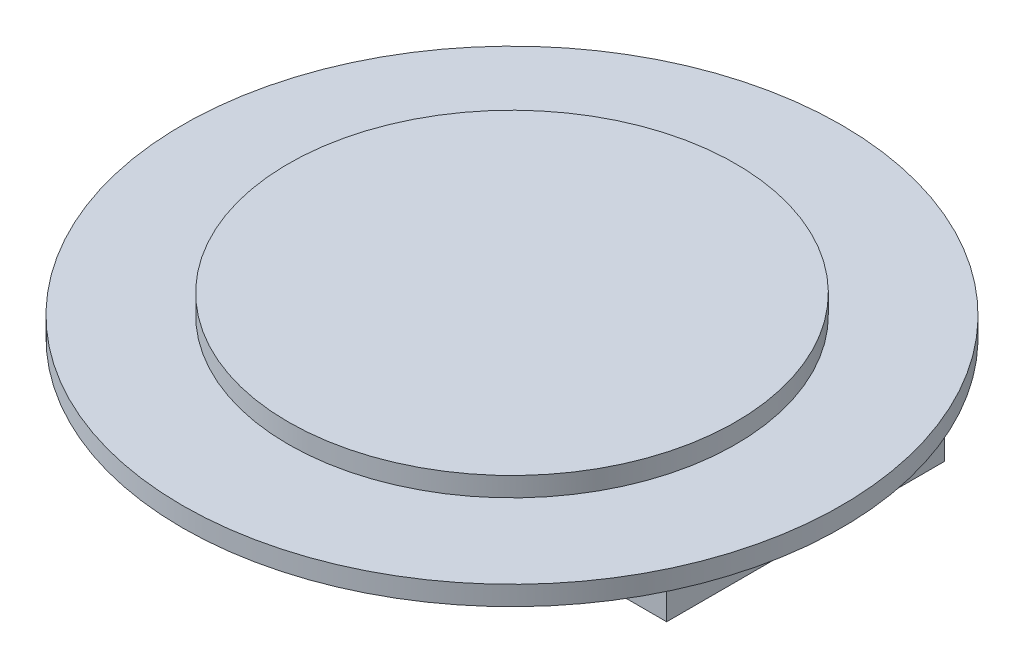
SolidWorks part; units mm, degrees
ref_plane "Front Plane" through (0, 0, 0) normal (0, 0, 1) x (1, 0, 0)
ref_plane "Top Plane" through (0, 0, 0) normal (0, 1, 0) x (1, 0, 0)
ref_plane "Right Plane" through (0, 0, 0) normal (1, 0, 0) x (0, 0, -1)
sketch "Sketch1" plane through (0, 0, 0) normal (0, 1, 0) x (1, 0, 0)
  circle A0 centre (0, 0) radius 17
  dimension "D1" = 34
extrude "Boss-Extrude1" add sketch "Sketch1" along normal blind 1
sketch "Sketch2" plane through (0, 0, 0) normal (0, -1, 0) x (1, 0, 0)
  line L1 (-5.8807, 4.7063) -> (12.685, 4.7063)
  line L2 (-5.8807, 4.7063) -> (-5.8807, -9.6323)
  line L3 (-5.8807, -9.6323) -> (12.685, -9.6323)
  line L4 (12.685, 4.7063) -> (12.685, -9.6323)
  line L5 (-5.8807, 4.7063) -> (12.685, -9.6323) construction
  line L6 (-5.8807, -9.6323) -> (12.685, 4.7063) construction
  point P0 (3.4022, -2.463)
extrude "Boss-Extrude2" add sketch "Sketch2" along normal blind 4
sketch "Sketch3" plane through (0, 1, 0) normal (0, 1, 0) x (1, 0, 0)
  circle A0 centre (0, 0) radius 11.5393
extrude "Boss-Extrude3" add sketch "Sketch3" along normal blind 1
